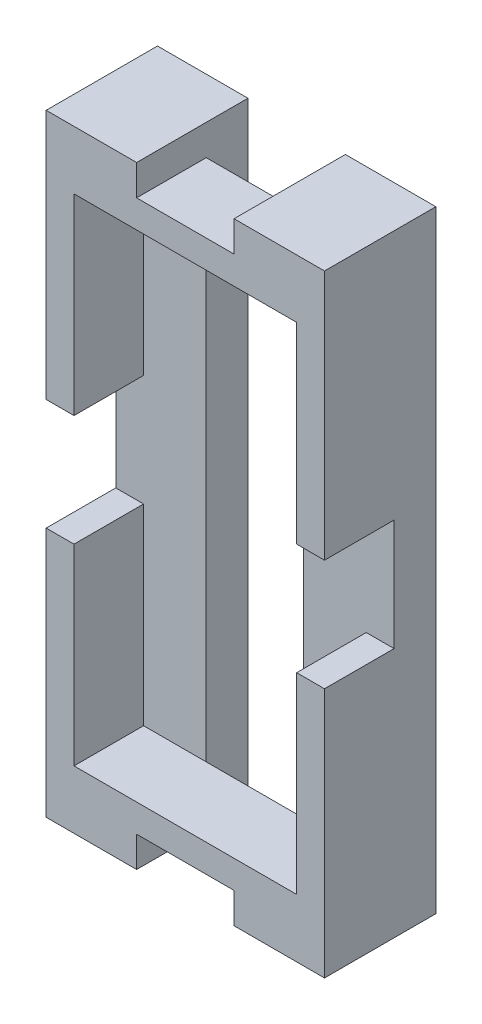
SolidWorks part; units mm, degrees
ref_plane "Front Plane" through (0, 0, 0) normal (0, 0, 1) x (1, 0, 0)
ref_plane "Top Plane" through (0, 0, 0) normal (0, 1, 0) x (1, 0, 0)
ref_plane "Right Plane" through (0, 0, 0) normal (1, 0, 0) x (0, 0, -1)
sketch "Sketch1" plane through (0, 0, 0) normal (0, 0, 1) x (1, 0, 0)
  line L1 (-5, -11) -> (5, -11)
  line L2 (-5, -11) -> (-5, 11)
  line L3 (-5, 11) -> (5, 11)
  line L4 (5, -11) -> (5, 11)
  line L5 (-5, -11) -> (5, 11) construction
  line L6 (-5, 11) -> (5, -11) construction
  point P0 (0, 0)
  dimension "D1" = 10
  dimension "D2" = 22
extrude "Boss-Extrude1" add sketch "Sketch1" along normal blind 4
sketch "Sketch2" plane through (0, 0, 0) normal (0, 0, -1) x (-1, 0, 0)
  line L0 (-5, 11) -> (5, 11) construction
  line L1 (-1.75, -11) -> (1.75, -11)
  line L2 (-1.75, -11) -> (-1.75, 11)
  line L3 (-1.75, 11) -> (1.75, 11)
  line L4 (1.75, -11) -> (1.75, 11)
  line L5 (-1.75, -11) -> (1.75, 11) construction
  line L6 (-1.75, 11) -> (1.75, -11) construction
  point P0 (0, 0)
  dimension "D1" = 3.5
extrude "slot" cut sketch "Sketch2" against normal blind 1.5
sketch "Sketch3" plane through (0, 0, 1.5) normal (0, 0, -1) x (-1, 0, 0)
  line L0 (1.75, -11) -> (1.75, 11) construction
  line L1 (-1.75, 11) -> (1.75, 11)
  line L2 (-1.75, 11) -> (-1.75, 9.9)
  line L3 (-1.75, 9.9) -> (1.75, 9.9)
  line L4 (1.75, 11) -> (1.75, 9.9)
  line L6 (-1.75, -11) -> (1.75, -11)
  line L7 (-1.75, -11) -> (-1.75, -9.9)
  line L8 (-1.75, -9.9) -> (1.75, -9.9)
  line L9 (1.75, -11) -> (1.75, -9.9)
  dimension "D1" = 1.1
  dimension "D2" = 1.1
extrude "Cut-Extrude2" cut sketch "Sketch3" against normal up to surface (2.5 mm away) up to face at (0, 0, 4)
sketch "Sketch4" plane through (0, 0, 4) normal (0, 0, 1) x (1, 0, 0)
  line L0 (-1.75, 9.9) -> (1.75, 9.9) construction
  line L1 (-4, -8.9) -> (4, -8.9)
  line L2 (-4, -8.9) -> (-4, 8.9)
  line L3 (-4, 8.9) -> (4, 8.9)
  line L4 (4, -8.9) -> (4, 8.9)
  line L5 (-4, -8.9) -> (4, 8.9) construction
  line L6 (-4, 8.9) -> (4, -8.9) construction
  line L7 (-5, 11) -> (-5, -11) construction
  point P0 (0, 0)
  dimension "D1" = 1
  dimension "D2" = 1
extrude "Cut-Extrude3" cut sketch "Sketch4" against normal up to surface (2.5 mm away) up to face at (0, 0, 1.5)
sketch "Sketch5" plane through (-4, 0, 0) normal (1, 0, 0) x (0, 0, -1)
  line L0 (-4, -11) -> (-4, 11) construction
  line L1 (-4, 2) -> (-1.5, 2)
  line L2 (-4, 2) -> (-4, -2)
  line L3 (-4, -2) -> (-1.5, -2)
  line L4 (-1.5, 2) -> (-1.5, -2)
  line L5 (-1.5, 8.9) -> (-1.5, -8.9) construction
  dimension "D1" = 4
  dimension "D2" = 2.5
  dimension "D3" = 2
sketch "Sketch6" plane through (-5, 0, 0) normal (-1, 0, 0) x (0, 0, 1)
  line L1 (1.5, 2) -> (4, 2)
  line L2 (1.5, 2) -> (1.5, -2)
  line L3 (1.5, -2) -> (4, -2)
  line L4 (4, 2) -> (4, -2)
extrude "Cut-Extrude4" cut sketch "Sketch6" against normal up to surface (10 mm away) up to face at (5, 0, 2)
